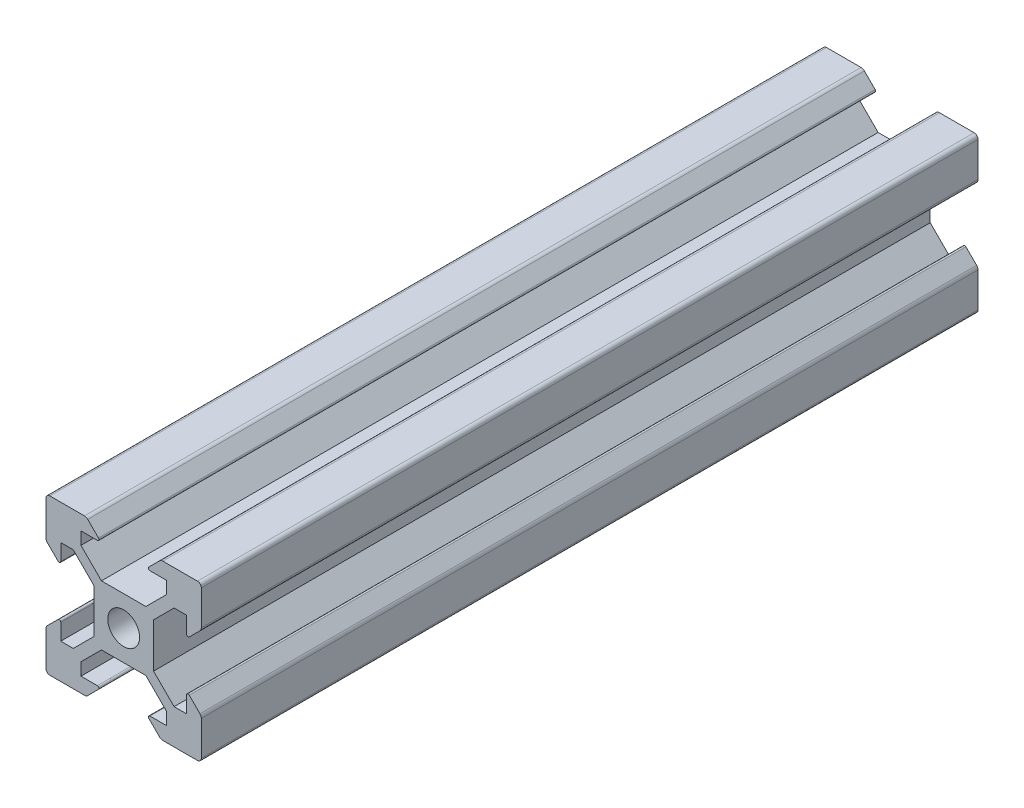
SolidWorks part; units mm, degrees
material "6063-T5"
ref_plane "Front Plane" through (0, 0, 0) normal (1, 0, 0) x (0, 1, 0)
ref_plane "Top Plane" through (0, 0, 0) normal (0, 0, 1) x (0, 1, 0)
ref_plane "Right Plane" through (0, 0, 0) normal (0, 1, 0) x (-1, 0, 0)
sketch "Sketch1" plane through (0, 0, 0) normal (0, 0, 1) x (0, 1, 0)
  line L0 (0, 0) -> (-10, 10) construction
  line L5 (-2.8601, -3.85) -> (2.8601, -3.85)
  line L6 (-3.85, -2.8601) -> (-3.85, 2.8601)
  line L11 (-2.8601, 3.85) -> (2.8601, 3.85)
  line L12 (3.85, -2.8601) -> (3.85, 2.8601)
  line L15 (-9.5, 10) -> (-5.0485, 10)
  line L16 (-4.6243, 9.8243) -> (-3.2414, 8.4414)
  line L17 (-3.3828, 8.1) -> (-5.5, 8.1)
  line L18 (-5.5, 8.1) -> (-5.5, 6.4899)
  line L19 (-5.5, 6.4899) -> (-2.8601, 3.85)
  line L20 (-6.4899, 5.5) -> (-3.85, 2.8601)
  line L21 (-10, 9.5) -> (-10, 5.0485)
  line L22 (-8.1, 5.5) -> (-6.4899, 5.5)
  line L23 (-8.1, 3.3828) -> (-8.1, 5.5)
  line L24 (-9.8243, 4.6243) -> (-8.4414, 3.2414)
  line L25 (10, 9.5) -> (10, 5.0485)
  line L26 (9.8243, 4.6243) -> (8.4414, 3.2414)
  line L27 (8.1, 3.3828) -> (8.1, 5.5)
  line L28 (8.1, 5.5) -> (6.4899, 5.5)
  line L29 (6.4899, 5.5) -> (3.85, 2.8601)
  line L30 (5.5, 6.4899) -> (2.8601, 3.85)
  line L31 (9.5, 10) -> (5.0485, 10)
  line L32 (5.5, 8.1) -> (5.5, 6.4899)
  line L33 (3.3828, 8.1) -> (5.5, 8.1)
  line L34 (4.6243, 9.8243) -> (3.2414, 8.4414)
  line L35 (9.5, -10) -> (5.0485, -10)
  line L36 (4.6243, -9.8243) -> (3.2414, -8.4414)
  line L37 (3.3828, -8.1) -> (5.5, -8.1)
  line L38 (5.5, -8.1) -> (5.5, -6.4899)
  line L39 (5.5, -6.4899) -> (2.8601, -3.85)
  line L40 (6.4899, -5.5) -> (3.85, -2.8601)
  line L41 (10, -9.5) -> (10, -5.0485)
  line L42 (8.1, -5.5) -> (6.4899, -5.5)
  line L43 (8.1, -3.3828) -> (8.1, -5.5)
  line L44 (9.8243, -4.6243) -> (8.4414, -3.2414)
  line L45 (-10, -9.5) -> (-10, -5.0485)
  line L46 (-9.8243, -4.6243) -> (-8.4414, -3.2414)
  line L47 (-8.1, -3.3828) -> (-8.1, -5.5)
  line L48 (-8.1, -5.5) -> (-6.4899, -5.5)
  line L49 (-6.4899, -5.5) -> (-3.85, -2.8601)
  line L50 (-5.5, -6.4899) -> (-2.8601, -3.85)
  line L51 (-9.5, -10) -> (-5.0485, -10)
  line L52 (-5.5, -8.1) -> (-5.5, -6.4899)
  line L53 (-3.3828, -8.1) -> (-5.5, -8.1)
  line L54 (-4.6243, -9.8243) -> (-3.2414, -8.4414)
  circle A1 centre (0, 0) radius 2.05
  arc A2 (-10, -9.5) -> (-9.5, -10) centre (-9.5, -9.5) ccw
  arc A3 (9.5, -10) -> (10, -9.5) centre (9.5, -9.5) ccw
  arc A4 (10, 9.5) -> (9.5, 10) centre (9.5, 9.5) ccw
  arc A5 (-10, 9.5) -> (-9.5, 10) centre (-9.5, 9.5) cw
  arc A6 (-3.2414, 8.4414) -> (-3.3828, 8.1) centre (-3.3828, 8.3) cw
  arc A7 (3.3828, 8.1) -> (3.2414, 8.4414) centre (3.3828, 8.3) cw
  arc A8 (8.4414, 3.2414) -> (8.1, 3.3828) centre (8.3, 3.3828) cw
  arc A9 (8.1, -3.3828) -> (8.4414, -3.2414) centre (8.3, -3.3828) cw
  arc A10 (3.2414, -8.4414) -> (3.3828, -8.1) centre (3.3828, -8.3) cw
  arc A11 (-3.3828, -8.1) -> (-3.2414, -8.4414) centre (-3.3828, -8.3) cw
  arc A12 (-8.4414, -3.2414) -> (-8.1, -3.3828) centre (-8.3, -3.3828) cw
  arc A13 (-8.1, 3.3828) -> (-8.4414, 3.2414) centre (-8.3, 3.3828) cw
  arc A14 (5.0485, 10) -> (4.6243, 9.8243) centre (5.0485, 9.4) ccw
  arc A15 (10, 5.0485) -> (9.8243, 4.6243) centre (9.4, 5.0485) cw
  arc A16 (10, -5.0485) -> (9.8243, -4.6243) centre (9.4, -5.0485) ccw
  arc A17 (5.0485, -10) -> (4.6243, -9.8243) centre (5.0485, -9.4) cw
  arc A18 (-5.0485, -10) -> (-4.6243, -9.8243) centre (-5.0485, -9.4) ccw
  arc A19 (-10, -5.0485) -> (-9.8243, -4.6243) centre (-9.4, -5.0485) cw
  arc A20 (-5.0485, 10) -> (-4.6243, 9.8243) centre (-5.0485, 9.4) cw
  arc A21 (-10, 5.0485) -> (-9.8243, 4.6243) centre (-9.4, 5.0485) ccw
  point P0 (0, 0)
  point P56 (0, 0)
  point P64 (-2.9, 8.1)
  point P79 (-8.1, 2.9)
  point P94 (-4.8, 10)
  point P97 (-10, 4.8)
  dimension "D3" = 7.7
  dimension "D2" = 4.1
  dimension "D9" = 0.5
  dimension "D10" = 0.2
  dimension "D11" = 0.6
  dimension "D1" = 10
  dimension "D4" = 7.1
  dimension "D5" = 1.4
  dimension "D6" = 4.5
  dimension "D7" = 1.9
  dimension "D8" = 4
extrude "Boss-Extrude1" add sketch "Sketch1" along normal blind 100
